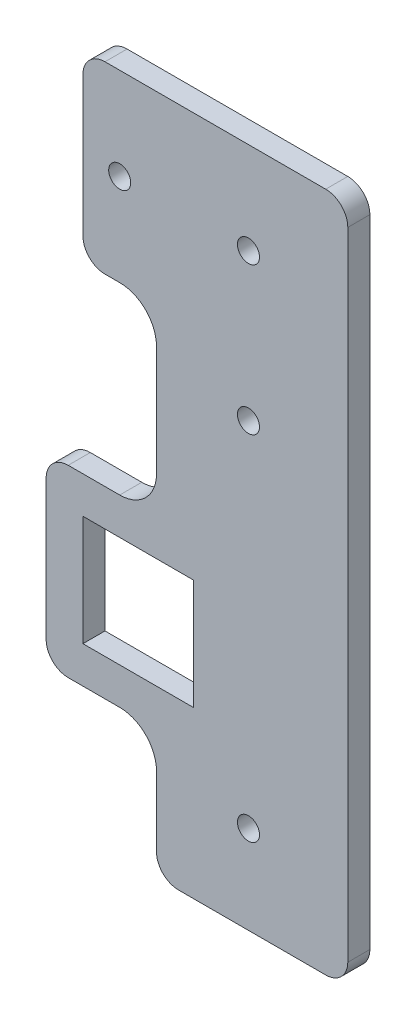
SolidWorks part; units mm, degrees
material "Thornel Mat VMA"
ref_plane "前视基准面" through (0, 0, 0) normal (0, 0, 1) x (1, 0, 0)
ref_plane "上视基准面" through (0, 0, 0) normal (0, 1, 0) x (1, 0, 0)
ref_plane "右视基准面" through (0, 0, 0) normal (1, 0, 0) x (0, 0, -1)
sketch "草图1" plane through (0, 0, 0) normal (0, 0, 1) x (1, 0, 0)
  line L0 (0, 0) -> (13.5, 0) construction
  line L1 (0, 0) -> (0, -80) construction
  line L2 (-7.5, 7.5) -> (-7.5, -80) construction
  line L3 (-7.5, 7.5) -> (13.5, 7.5) construction
  line L4 (7.5, -7.5) -> (7.5, -80) construction
  line L5 (7.5, -7.5) -> (13.5, -7.5) construction
  line L6 (0, 0) -> (-22.5, 0) construction
  line L7 (13.5, -80) -> (13.5, 12.5)
  line L8 (13.5, 12.5) -> (-22.5, 12.5)
  line L9 (-22.5, 12.5) -> (-22.5, -12.5)
  line L10 (-22.5, -12.5) -> (-12.5, -12.5)
  line L11 (-12.5, -12.5) -> (-12.5, -37.5)
  line L12 (-12.5, -37.5) -> (-27.5, -37.5)
  line L13 (-27.5, -37.5) -> (-27.5, -62.5)
  line L14 (-27.5, -62.5) -> (-12.5, -62.5)
  line L15 (0, 0) -> (0, -40.2329) construction
  line L16 (-7.5, -42.5) -> (-22.5, -42.5)
  line L17 (-7.5, -42.5) -> (-7.5, -57.5)
  line L18 (-7.5, -57.5) -> (-22.5, -57.5)
  line L19 (-22.5, -42.5) -> (-22.5, -57.5)
  line L20 (-7.5, 7.5) -> (-7.5, -40.2329) construction
  line L21 (7.5, -7.5) -> (7.5, -40.2329) construction
  line L22 (-12.5, -62.5) -> (-12.5, -80)
  line L23 (-12.5, -80) -> (13.5, -80)
  line L24 (-7.5, 7.5) -> (46.235, 7.5) construction
  line L25 (0, 0) -> (46.235, 0) construction
  line L26 (7.5, -7.5) -> (46.235, -7.5) construction
  circle A0 centre (0, 0) radius 1.5
  circle A1 centre (0, -20) radius 1.5
  circle A2 centre (0, -68) radius 1.5
  circle A3 centre (-17.5, 0) radius 1.5
  point P20 (-7.5, -50)
  point P27 (-27.5, -50)
  point P28 (-22.5, -50)
  point P38 (13.5, 7.5)
  point P41 (13.5, 0)
  point P43 (13.5, -7.5)
  dimension "D12" = 20
  dimension "D13" = 3
  dimension "D14" = 18
  dimension "D15" = 5
  dimension "D1" = 7.5
  dimension "D2" = 7.5
  dimension "D3" = 15
  dimension "D4" = 6
  dimension "D5" = 5
  dimension "D6" = 5
  dimension "D7" = 15
  dimension "D8" = 50
  dimension "D9" = 5
  dimension "D10" = 5
  dimension "D11" = 30
extrude "凸台-拉伸1" add sketch "草图1" along normal blind 3
fillet "圆角1" radius 5 3 edges at (-12.5, -62.5, 1.5) (-12.5, -12.5, 1.5) (-12.5, -37.5, 1.5)
fillet "圆角2" radius 3 7 edges at (13.5, -80, 1.5) (-12.5, -80, 1.5) (-27.5, -62.5, 1.5) (-27.5, -37.5, 1.5) (-22.5, -12.5, 1.5) (-22.5, 12.5, 1.5) (13.5, 12.5, 1.5)
